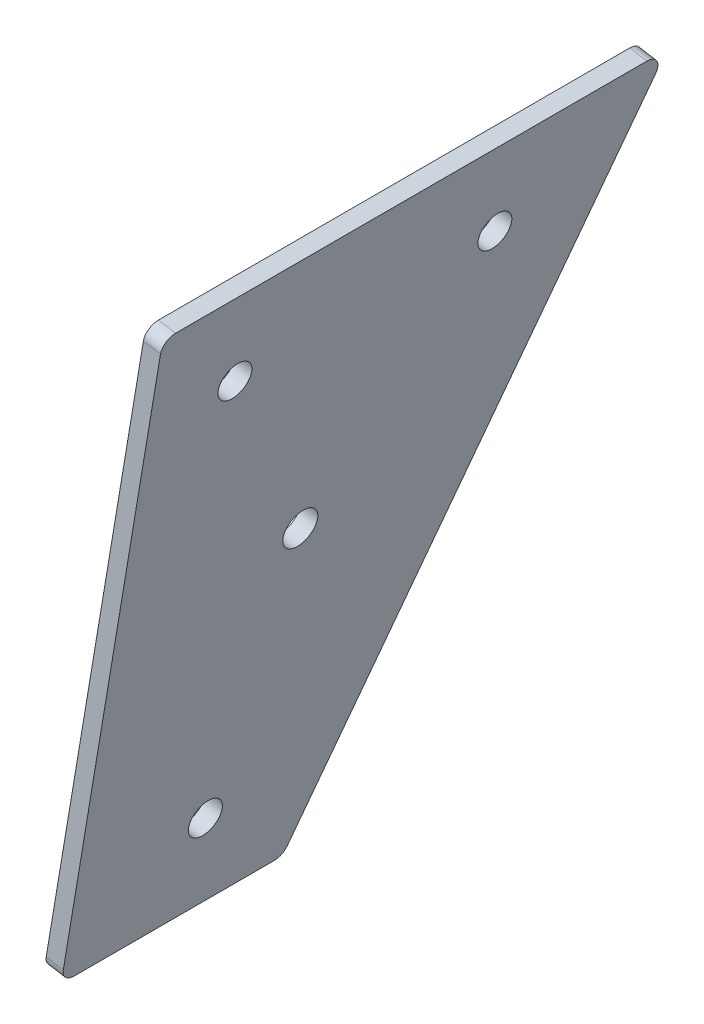
SolidWorks part; units mm, degrees
ref_plane "Front Plane" through (0, 0, 0) normal (0, 0, 1) x (1, 0, 0)
ref_plane "Top Plane" through (0, 0, 0) normal (0, 1, 0) x (1, 0, 0)
ref_plane "Right Plane" through (0, 0, 0) normal (1, 0, 0) x (0, 0, -1)
sketch "Sketch5" plane through (59.169, -9.8811, 0) normal (0.9863, -0.1647, 0) x (0, 0, -1)
  line L0 (-51.1, 106.1357) -> (65.3955, 106.1357)
  line L1 (65.3955, 106.1357) -> (0, -36.0475)
  line L2 (0, -36.0475) -> (-51.1, -36.0475)
  line L3 (-51.1, -36.0475) -> (-51.1, 106.1357)
  circle A0 centre (-31.1, 86.1357) radius 3.875
  circle A1 centre (28.9, 86.1357) radius 3.875
  circle A2 centre (-8.6, 41.1357) radius 4
  circle A3 centre (-21.1, -16.0475) radius 3.875
extrude "Boss-Extrude2" add sketch "Sketch5" along normal blind 4 from offset 10
fillet "Fillet1" radius 3 2 edges at (65.0675, -47.4128, 0) (65.0675, -47.4128, 51.1)
fillet "Fillet2" radius 3 2 edges at (88.4875, 92.8282, -65.3955) (88.4875, 92.8282, 51.1)
